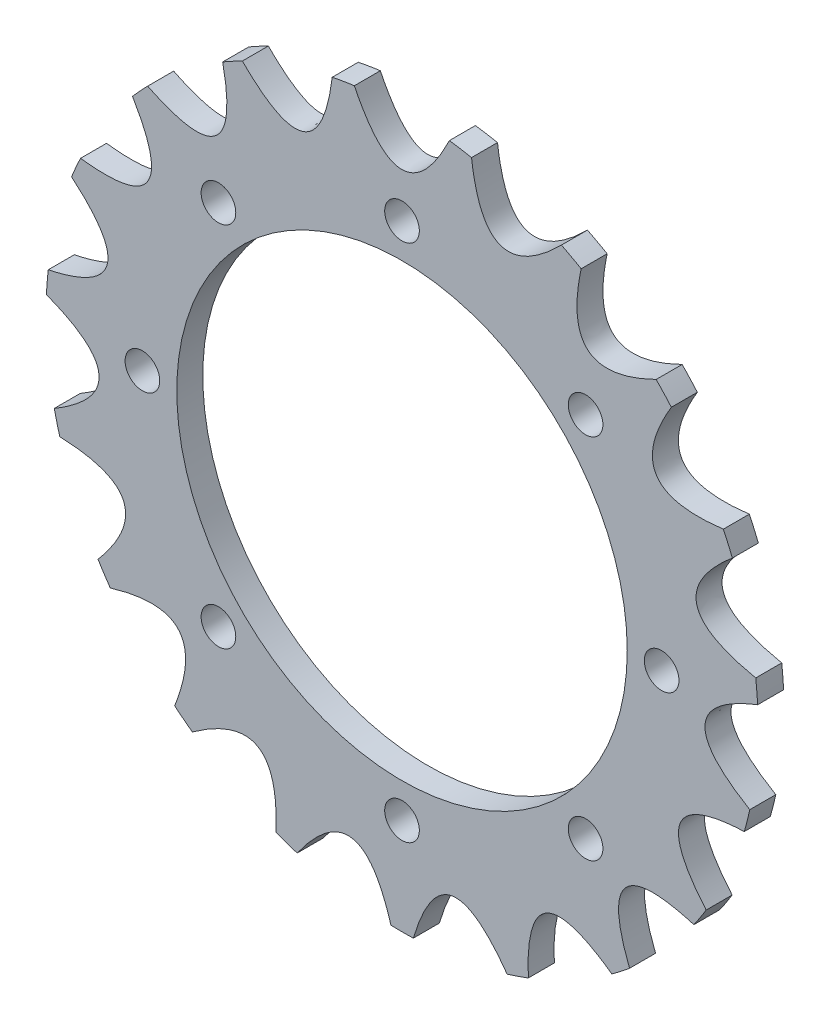
SolidWorks part; units mm, degrees
ref_plane "Спереди" through (0, 0, 0) normal (0, 0, 1) x (1, 0, 0)
ref_plane "Сверху" through (0, 0, 0) normal (0, 1, 0) x (1, 0, 0)
ref_plane "Справа" through (0, 0, 0) normal (1, 0, 0) x (0, 0, -1)
sketch "Эскиз1" plane through (0, 0, 0) normal (0, 0, 1) x (1, 0, 0)
  circle A0 centre (0, 0) radius 26
  arc A1 (-5.5, 40.7303) -> (-8.0527, 40.3034) centre (0, 0) ccw
  arc A2 (8.0231, 40.3093) -> (5.4701, 40.7344) centre (0, 0) ccw
  arc A3 (20.6768, 35.5201) -> (18.4001, 36.7511) centre (0, 0) ccw
  arc A4 (31.0899, 26.8818) -> (29.3362, 28.7853) centre (0, 0) ccw
  arc A5 (38.1338, 15.3304) -> (37.0933, 17.7002) centre (0, 0) ccw
  arc A6 (41.0454, 2.1177) -> (40.8307, 4.697) centre (0, 0) ccw
  arc A7 (39.5091, -11.3244) -> (40.1435, -8.8152) centre (0, 0) ccw
  arc A8 (33.6913, -23.5394) -> (35.1061, -21.3722) centre (0, 0) ccw
  arc A9 (24.2226, -33.2035) -> (26.2644, -31.6131) centre (0, 0) ccw
  arc A10 (12.129, -39.2696) -> (14.5766, -38.4283) centre (0, 0) ccw
  arc A11 (-1.279, -41.0801) -> (1.3092, -41.0791) centre (0, 0) ccw
  arc A12 (-14.5484, -38.439) -> (-12.1001, -39.2784) centre (0, 0) ccw
  arc A13 (-26.2412, -31.6324) -> (-24.1982, -33.2213) centre (0, 0) ccw
  arc A14 (-35.0904, -21.3979) -> (-33.674, -23.5642) centre (0, 0) ccw
  arc A15 (-40.137, -8.8447) -> (-39.5008, -11.3534) centre (0, 0) ccw
  arc A16 (-40.8342, 4.667) -> (-41.0469, 2.0876) centre (0, 0) ccw
  arc A17 (-37.1063, 17.673) -> (-38.1451, 15.3024) centre (0, 0) ccw
  arc A18 (-29.3574, 28.7638) -> (-31.1096, 26.859) centre (0, 0) ccw
  arc A19 (-18.4271, 36.7376) -> (-20.7029, 35.5049) centre (0, 0) ccw
  circle A20 centre (0, 29.9666) radius 2
  circle A21 centre (21.1896, 21.1896) radius 2
  circle A22 centre (29.9666, 0) radius 2
  circle A23 centre (21.1896, -21.1896) radius 2
  circle A24 centre (0, -29.9666) radius 2
  circle A25 centre (-21.1896, -21.1896) radius 2
  circle A26 centre (-29.9666, 0) radius 2
  circle A27 centre (-21.1896, 21.1896) radius 2
  spline S0 degree 2 poles (-5.5, 40.7303) (0.0024, 29.4676) (5.4701, 40.7344) knots 0 0 0 1 1 1
  spline S1 degree 2 poles (8.0231, 40.3093) (9.5704, 27.8702) (18.4001, 36.7511) knots 0 0 0 1 1 1
  spline S2 degree 2 poles (20.6768, 35.5201) (18.1013, 23.2526) (29.3362, 28.7853) knots 0 0 0 1 1 1
  spline S3 degree 2 poles (31.0899, 26.8818) (24.6706, 16.1153) (37.0933, 17.7002) knots 0 0 0 1 1 1
  spline S4 degree 2 poles (38.1338, 15.3304) (28.5665, 7.2315) (40.8307, 4.697) knots 0 0 0 1 1 1
  spline S5 degree 2 poles (41.0454, 2.1177) (29.3668, -2.4358) (40.1435, -8.8152) knots 0 0 0 1 1 1
  spline S6 degree 2 poles (39.5091, -11.3244) (26.9847, -11.8392) (35.1061, -21.3722) knots 0 0 0 1 1 1
  spline S7 degree 2 poles (33.6913, -23.5394) (21.6784, -19.9597) (26.2644, -31.6131) knots 0 0 0 1 1 1
  spline S8 degree 2 poles (24.2226, -33.2035) (14.0229, -25.9172) (14.5766, -38.4283) knots 0 0 0 1 1 1
  spline S9 degree 2 poles (12.129, -39.2696) (4.8478, -29.0661) (1.3092, -41.0791) knots 0 0 0 1 1 1
  spline S10 degree 2 poles (-1.279, -41.0801) (-4.8526, -29.0653) (-12.1001, -39.2784) knots 0 0 0 1 1 1
  spline S11 degree 2 poles (-14.5484, -38.439) (-14.0272, -25.9149) (-24.1982, -33.2213) knots 0 0 0 1 1 1
  spline S12 degree 2 poles (-26.2412, -31.6324) (-21.6817, -19.9561) (-33.674, -23.5642) knots 0 0 0 1 1 1
  spline S13 degree 2 poles (-35.0904, -21.3979) (-26.9866, -11.8348) (-39.5008, -11.3534) knots 0 0 0 1 1 1
  spline S14 degree 2 poles (-40.137, -8.8447) (-29.3672, -2.431) (-41.0469, 2.0876) knots 0 0 0 1 1 1
  spline S15 degree 2 poles (-40.8342, 4.667) (-28.5653, 7.2362) (-38.1451, 15.3024) knots 0 0 0 1 1 1
  spline S16 degree 2 poles (-37.1063, 17.673) (-24.668, 16.1193) (-31.1096, 26.859) knots 0 0 0 1 1 1
  spline S17 degree 2 poles (-29.3574, 28.7638) (-18.0975, 23.2556) (-20.7029, 35.5049) knots 0 0 0 1 1 1
  spline S18 degree 2 poles (-18.4271, 36.7376) (-9.5658, 27.8718) (-8.0527, 40.3034) knots 0 0 0 1 1 1
extrude "Вытянуть1" add sketch "Эскиз1" along normal blind 3
